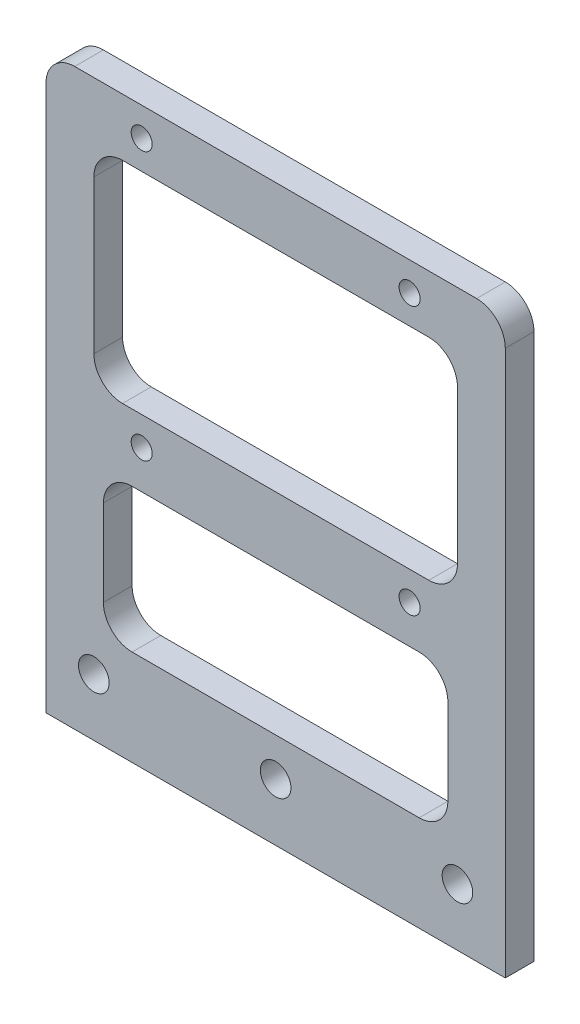
SolidWorks part; units mm, degrees
material "Thornel Mat VMA"
ref_plane "前视基准面" through (0, 0, 0) normal (0, 0, 1) x (1, 0, 0)
ref_plane "上视基准面" through (0, 0, 0) normal (0, 1, 0) x (1, 0, 0)
ref_plane "右视基准面" through (0, 0, 0) normal (1, 0, 0) x (0, 0, -1)
sketch "草图1" plane through (0, 0, 0) normal (0, 0, 1) x (1, 0, 0)
  line L0 (0, 62.0311) -> (0, -32.7104) construction
  line L1 (-50.9594, 0) -> (46.631, 0) construction
  line L2 (-18, 10) -> (-3.7914, 10)
  line L3 (-24, 0) -> (24, 0)
  line L4 (-24, 0) -> (-24, 60)
  line L5 (-24, 60) -> (24, 60)
  line L6 (24, 0) -> (24, 60)
  line L7 (-19, 54) -> (19, 54)
  line L8 (-19, 54) -> (-19, 32)
  line L9 (-19, 32) -> (19, 32)
  line L10 (19, 54) -> (19, 32)
  line L11 (-19, 54) -> (19, 32) construction
  line L12 (-19, 32) -> (19, 54) construction
  line L13 (-3.7914, 10) -> (3.7914, 10)
  line L14 (3.7914, 10) -> (18, 10)
  line L15 (18, 10) -> (18, 25)
  line L16 (18, 25) -> (-18, 25)
  line L17 (-18, 25) -> (-18, 10)
  line L18 (-19, 6) -> (0, 6) construction
  circle A0 centre (0, 6) radius 1.6
  circle A1 centre (-19, 6) radius 1.6
  circle A2 centre (19, 6) radius 1.6
  circle A3 centre (-14, 57) radius 1.1
  circle A4 centre (-14, 29) radius 1.1
  circle A5 centre (14, 57) radius 1.1
  circle A6 centre (14, 29) radius 1.1
  point P28 (0, 43)
  dimension "D1" = 3.2
  dimension "D2" = 38
  dimension "D3" = 6
  dimension "D5" = 2.2
  dimension "D6" = 28
  dimension "D7" = 28
  dimension "D10" = 60
  dimension "D8" = 3
  dimension "D9" = 10
  dimension "D11" = 3
  dimension "D12" = 3
  dimension "D13" = 5
  dimension "D14" = 4
  dimension "D15" = 6
  dimension "D16" = 4
extrude "凸台-拉伸1" add sketch "草图1" along normal blind 3
fillet "圆角1" radius 3 6 edges at (-24, 60, 1.5) (24, 60, 1.5) (19, 32, 1.5) (19, 54, 1.5) (-19, 54, 1.5) (-19, 32, 1.5)
fillet "圆角2" radius 3 4 edges at (18, 25, 1.5) (-18, 25, 1.5) (18, 10, 1.5) (-18, 10, 1.5)
